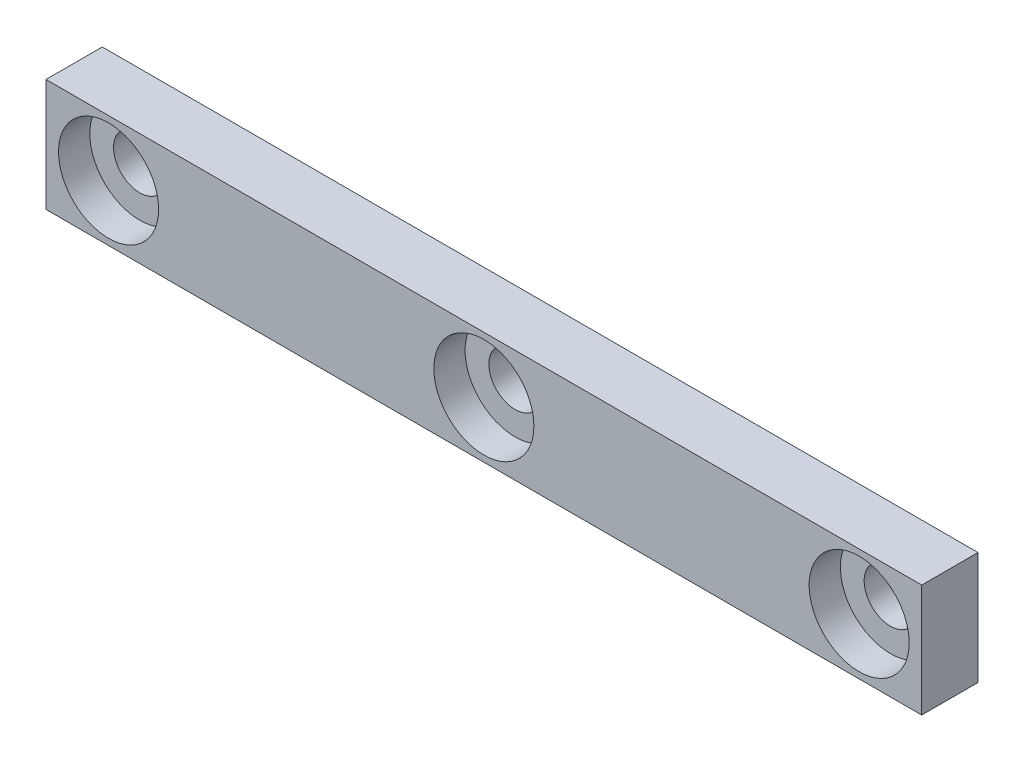
SolidWorks part; units mm, degrees
ref_plane "前基準面" through (0, 0, 0) normal (0, 0, 1) x (1, 0, 0)
ref_plane "上基準面" through (0, 0, 0) normal (0, 1, 0) x (1, 0, 0)
ref_plane "右基準面" through (0, 0, 0) normal (1, 0, 0) x (0, 0, -1)
sketch "草圖1" plane through (0, 0, 0) normal (0, 0, 1) x (1, 0, 0)
  line L1 (-19.3577, 2.8426) -> (50.6423, 2.8426)
  line L2 (-19.3577, 2.8426) -> (-19.3577, -6.1574)
  line L3 (-19.3577, -6.1574) -> (50.6423, -6.1574)
  line L4 (50.6423, 2.8426) -> (50.6423, -6.1574)
  circle A0 centre (-14.3577, -1.6574) radius 2.1
  circle A1 centre (15.6423, -1.6574) radius 2.1
  circle A2 centre (45.6423, -1.6574) radius 2.1
  dimension "D9" = 4.2
  dimension "D10" = 4.2
  dimension "D11" = 4.2
  dimension "D1" = 70
  dimension "D2" = 9
  dimension "D3" = 5
  dimension "D4" = 30
  dimension "D5" = 5
  dimension "D6" = 4.5
  dimension "D7" = 4.5
  dimension "D8" = 4.5
extrude "填料-伸長1" add sketch "草圖1" along normal blind 4.5
sketch "草圖3" plane through (0, 0, 4.5) normal (0, 0, 1) x (1, 0, 0)
  circle A0 centre (-14.3577, -1.6574) radius 4
  circle A1 centre (15.6423, -1.6574) radius 4
  circle A2 centre (45.6423, -1.6574) radius 4
  dimension "D1" = 8
  dimension "D2" = 8
  dimension "D3" = 8
extrude "除料-伸長1" cut sketch "草圖3" against normal blind 2.5
